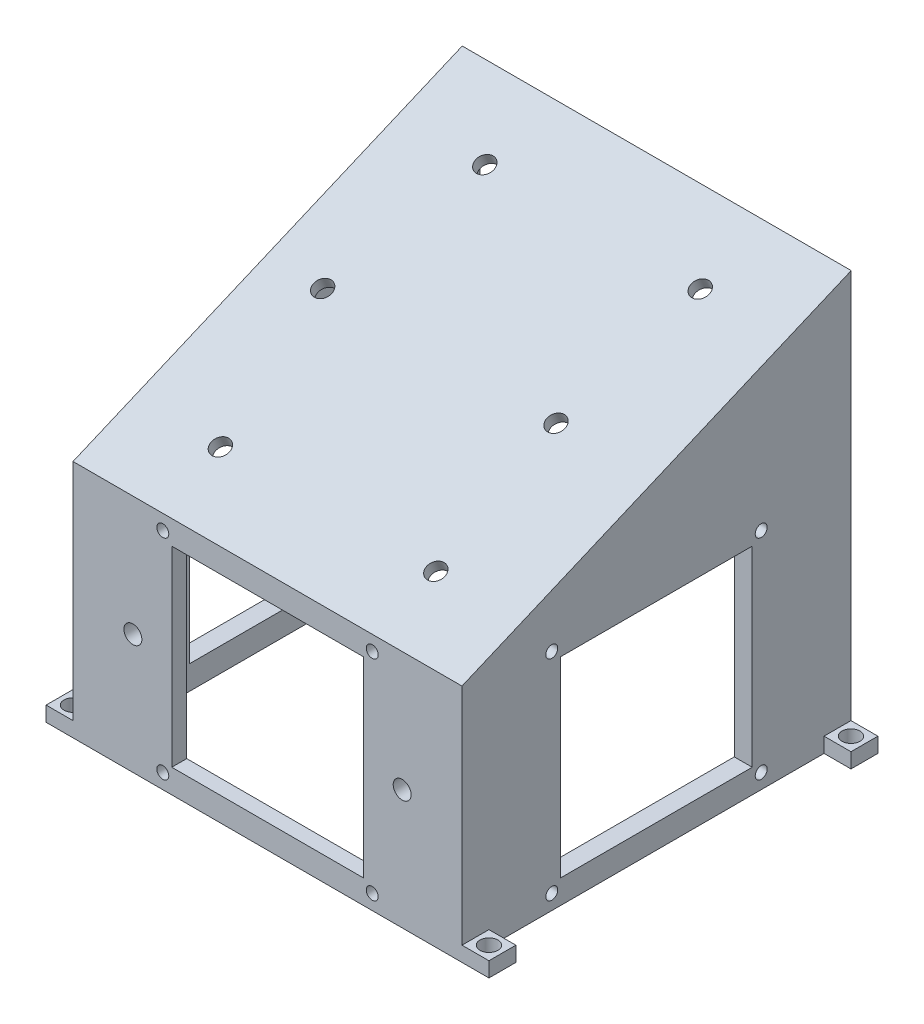
SolidWorks part; units mm, degrees
ref_plane "前视基准面" through (0, 0, 0) normal (0, 0, 1) x (1, 0, 0)
ref_plane "上视基准面" through (0, 0, 0) normal (0, 1, 0) x (1, 0, 0)
ref_plane "右视基准面" through (0, 0, 0) normal (1, 0, 0) x (0, 0, -1)
sketch "草图1" plane through (0, 0, 0) normal (0, 1, 0) x (1, 0, 0)
  line L0 (-37, -30.25) -> (-34.3982, -30.25) construction
  line L1 (-32.5, 32.5) -> (32.5, 32.5)
  line L2 (-32.5, 32.5) -> (-32.5, -32.5)
  line L3 (-32.5, -32.5) -> (32.5, -32.5)
  line L4 (32.5, 32.5) -> (32.5, -32.5)
  line L5 (-32.5, 32.5) -> (32.5, -32.5) construction
  line L6 (-32.5, -32.5) -> (32.5, 32.5) construction
  line L7 (-32.5, 32.5) -> (-37, 32.5)
  line L8 (-32.5, 32.5) -> (-32.5, 28)
  line L9 (-32.5, 28) -> (-37, 28)
  line L10 (-37, 32.5) -> (-37, 28)
  line L11 (-32.5, -32.5) -> (-37, -32.5)
  line L12 (-32.5, -32.5) -> (-32.5, -28)
  line L13 (-32.5, -28) -> (-37, -28)
  line L14 (-37, -32.5) -> (-37, -28)
  line L15 (-34.75, -28) -> (-34.75, -50028) construction
  line L16 (-32.5, 28) -> (-37, 32.5) construction
  line L17 (32.5, -28) -> (37, -32.5) construction
  line L18 (32.5, -32.5) -> (37, -32.5)
  line L19 (32.5, -32.5) -> (32.5, -28)
  line L20 (32.5, -28) -> (37, -28)
  line L21 (37, -32.5) -> (37, -28)
  line L22 (34.75, 32.5) -> (34.75, -49967.5) construction
  line L23 (32.5, 32.5) -> (37, 32.5)
  line L24 (32.5, 32.5) -> (32.5, 28)
  line L25 (32.5, 28) -> (37, 28)
  line L26 (37, 32.5) -> (37, 28)
  line L27 (32.5, 32.5) -> (37, 28) construction
  circle A0 centre (-34.75, -30.25) radius 1.5
  circle A1 centre (-34.75, 30.25) radius 1.5
  circle A2 centre (34.75, -30.25) radius 1.5
  circle A3 centre (34.75, 30.25) radius 1.5
  circle A4 centre (-18, 24) radius 1.5
  circle A5 centre (18, 24) radius 1.5
  circle A6 centre (18, -24) radius 1.5
  circle A7 centre (-18, -24) radius 1.5
  circle A8 centre (-16, 0) radius 1.5
  circle A9 centre (23, 0) radius 1.5
  point P0 (0, 0)
  point P16 (-34.75, -28)
  point P31 (34.75, 32.5)
  dimension "D5" = 4.5
  dimension "D7" = 4.5
  dimension "D9" = 4.5
  dimension "D10" = 8.5
  dimension "D12" = 3
  dimension "D15" = 16.5
  dimension "D16" = 3
  dimension "D1" = 65
  dimension "D2" = 65
  dimension "D3" = 4.5
  dimension "D4" = 4.5
  dimension "D6" = 4.5
  dimension "D8" = 4.5
  dimension "D11" = 14.5
  dimension "D13" = 2
  dimension "D14" = 2
  dimension "D17" = 2
extrude "凸台-拉伸1" add sketch "草图1" along normal blind 2.5 contours L14 L11 L2 L13 A0 | L18 L21 L20 L4 A2 | L26 L23 L4 L25 A3 | L7 L10 L9 L2 A1
sketch "草图2" plane through (0, 0, 0) normal (0, -1, 0) x (-1, 0, 0)
  line L1 (32.5, -32.5) -> (29.5, -32.5)
  line L2 (32.5, -32.5) -> (32.5, 32.5)
  line L3 (32.5, 32.5) -> (29.5, 32.5)
  line L4 (29.5, -32.5) -> (29.5, 32.5)
  line L5 (-32.5, 32.5) -> (-29.5, 32.5)
  line L6 (-32.5, 32.5) -> (-32.5, -32.5)
  line L7 (-32.5, -32.5) -> (-29.5, -32.5)
  line L8 (-29.5, 32.5) -> (-29.5, -32.5)
  dimension "D1" = 3
  dimension "D2" = 65
  dimension "D3" = 3
extrude "凸台-拉伸2" add sketch "草图2" against normal blind 40
sketch "草图3" plane through (0, 0, 32.5) normal (0, 0, 1) x (1, 0, 0)
  line L0 (0, 0) -> (0, 50000) construction
  line L1 (-29.5, 0) -> (29.5, 0)
  line L2 (-29.5, 0) -> (-29.5, 40)
  line L3 (-29.5, 40) -> (29.5, 40)
  line L4 (29.5, 0) -> (29.5, 40)
  line L5 (0, 20) -> (37.8784, 20) construction
  line L6 (-16, 36) -> (16, 36)
  line L7 (-16, 36) -> (-16, 4)
  line L8 (-16, 4) -> (16, 4)
  line L9 (16, 36) -> (16, 4)
  line L10 (-16, 36) -> (16, 4) construction
  line L11 (-16, 4) -> (16, 36) construction
  circle A0 centre (-17.5, 37.5) radius 1
  circle A1 centre (17.5, 37.5) radius 1
  circle A2 centre (17.5, 2.5) radius 1
  circle A3 centre (-17.5, 2.5) radius 1
  circle A4 centre (-22.5, 20) radius 1.5
  circle A5 centre (22.5, 20) radius 1.5
  point P9 (0, 20)
  dimension "D4" = 1.5
  dimension "D8" = 22.5
  dimension "D1" = 32
  dimension "D2" = 32
  dimension "D3" = 4
  dimension "D5" = 1.5
  dimension "D6" = 2
  dimension "D7" = 2
  dimension "D9" = 2
extrude "凸台-拉伸4" add sketch "草图3" against normal blind 2.5 separate body
sketch "草图5" plane through (-32.5, 0, 0) normal (-1, 0, 0) x (0, 0, 1)
  line L0 (32.5, 40) -> (-19.6777, 62.1481)
  line L1 (32.5, 40) -> (-32.5, 40) construction
  line L2 (-19.6777, 62.1481) -> (-32.5435, 67.6093)
  line L3 (-32.5435, 67.6093) -> (-32.5, 40)
  line L5 (-32.5, 40) -> (32.5, 40)
  dimension "D1" = 23
extrude "凸台-拉伸5" add sketch "草图5" against normal blind 3 contours L5 L0 L2 L3
ref_plane "基准面1" through (0, 45.5824, 19.3486) normal (0, 0.9205, 0.3907) x (1, 0, 0)
sketch "草图8" plane through (32.5, 0, 0) normal (1, 0, 0) x (0, 0, -1)
  line L0 (-32.5, 40) -> (32.5, 40)
  line L1 (16.4253, 60.7676) -> (-55.1225, 30.3973) construction
  line L2 (-32.5, 40) -> (-32.5, 2.5) construction
  line L3 (32.5, 40) -> (32.5435, 67.6093)
  line L4 (32.5435, 67.6093) -> (32.5, 40) construction
  line L5 (32.5435, 67.6093) -> (-32.5, 40)
extrude "凸台-拉伸6" add sketch "草图8" against normal blind 3 contours L5 L0 L3
sketch "草图9" plane through (0, 45.5824, 19.3486) normal (0, 0.9205, 0.3907) x (1, 0, 0)
  line L1 (-32.5, -14.2872) -> (32.5, -14.2872)
  line L2 (-32.5, -14.2872) -> (-32.5, 56.3735)
  line L3 (-32.5, 56.3735) -> (32.5, 56.3735)
  line L4 (32.5, -14.2872) -> (32.5, 56.3735)
extrude "凸台-拉伸8" add sketch "草图9" against normal blind 1.8
sketch "草图12" plane through (-32.5, 0, 0) normal (-1, 0, 0) x (0, 0, 1)
  line L0 (0, 0) -> (0, 61.88) construction
  line L1 (0, 0) -> (50000, 0) construction
  line L3 (32.5, 40) -> (0, 40) construction
  line L6 (-16, 36) -> (16, 36)
  line L7 (-16, 36) -> (-16, 4)
  line L8 (-16, 4) -> (16, 4)
  line L9 (16, 36) -> (16, 4)
  line L10 (-16, 36) -> (16, 4) construction
  line L11 (-16, 4) -> (16, 36) construction
  circle A0 centre (-17.5, 37.5) radius 1
  circle A1 centre (17.5, 37.5) radius 1
  circle A2 centre (17.5, 2.5) radius 1
  circle A3 centre (-17.5, 2.5) radius 1
  point P6 (0, 20)
  dimension "D4" = 1.5
  dimension "D1" = 32
  dimension "D2" = 32
  dimension "D3" = 4
  dimension "D5" = 1.5
  dimension "D6" = 2
  dimension "D7" = 2
extrude "切除-拉伸2" cut sketch "草图12" against normal blind 65
sketch "草图13" plane through (32.5, 0, 0) normal (1, 0, 0) x (0, 0, -1)
  line L0 (32.5404, 65.6526) -> (32.5404, 67.608)
  line L1 (16.4253, 60.7676) -> (-55.1225, 30.3973) construction
  line L2 (32.5404, 67.608) -> (33.2468, 65.9524)
  line L3 (33.2468, 65.9524) -> (32.5404, 65.6526)
extrude "切除-拉伸6" cut sketch "草图13" against normal blind 65 contours L3 L0 L2
sketch "草图14" plane through (0, 45.5824, 19.3486) normal (0, 0.9205, 0.3907) x (1, 0, 0)
  line L0 (0, -14.2872) -> (0, -50014.2872) construction
  line L1 (32.5, -14.2872) -> (-32.5, -14.2872) construction
  circle A0 centre (18, -3.2872) radius 1.5
  circle A1 centre (16, 20.7128) radius 1.5
  circle A2 centre (18, 44.7128) radius 1.5
  circle A3 centre (-18, -3.2872) radius 1.5
  circle A5 centre (-18, 44.7128) radius 1.5
  circle A6 centre (-23, 20.7128) radius 1.5
  point P6 (0, -14.2872)
  dimension "D1" = 3
  dimension "D2" = 3
  dimension "D9" = 39
  dimension "D3" = 18
  dimension "D4" = 18
  dimension "D5" = 16
  dimension "D6" = 48
  dimension "D7" = 24
  dimension "D8" = 11
extrude "切除-拉伸8" cut sketch "草图14" against normal blind 1.8
